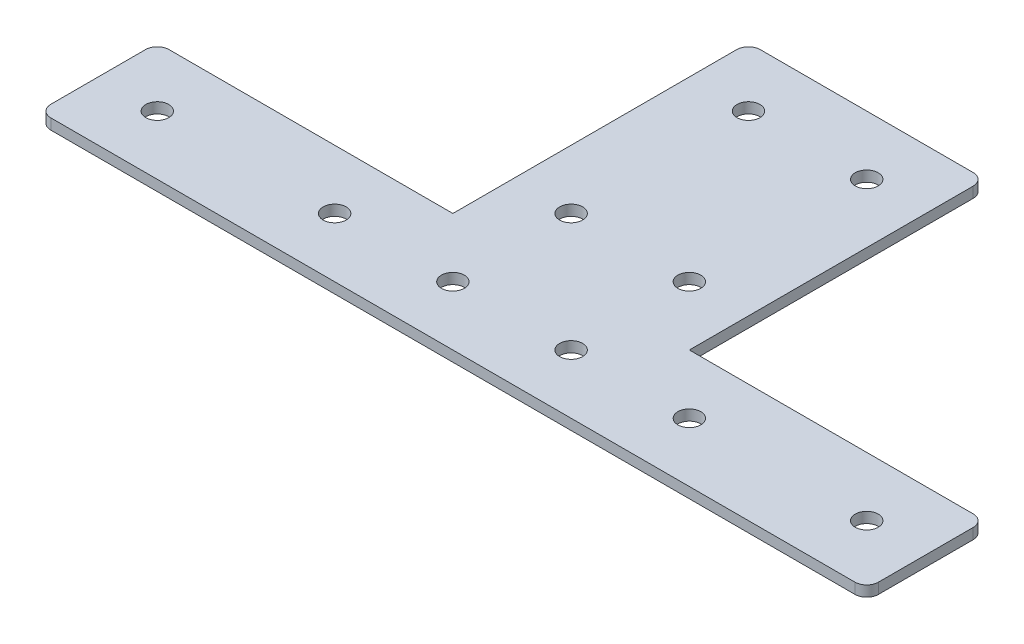
SolidWorks part; units mm, degrees
material "1060 Alloy"
ref_plane "Front Plane" through (0, 0, 0) normal (0, 0, 1) x (1, 0, 0)
ref_plane "Top Plane" through (0, 0, 0) normal (0, 1, 0) x (1, 0, 0)
ref_plane "Right Plane" through (0, 0, 0) normal (1, 0, 0) x (0, 0, -1)
sketch "Sketch1" plane through (0, 0, 0) normal (0, 1, 0) x (1, 0, 0)
  line L1 (0, 0) -> (88.9, 0)
  line L2 (0, 88.9) -> (0, 0)
  line L3 (12.7, 88.9) -> (12.7, 0) construction
  line L8 (25.4, 25.4) -> (88.9, 25.4)
  line L9 (88.9, 0) -> (88.9, 25.4)
  line L12 (0, 88.9) -> (25.4, 88.9)
  line L13 (25.4, 25.4) -> (25.4, 88.9)
  dimension "D1" = 25.4
  dimension "D2" = 88.9
extrude "Boss-Extrude1" add sketch "Sketch1" along normal blind 2.286
ref_plane "Plane1" through (12.7, 0, 0) normal (-1, 0, 0) x (0, 0, 1)
sketch "Sketch3" plane through (0, 2.286, 0) normal (0, 1, 0) x (1, 0, 0)
  line L0 (0, 12.7) -> (88.9, 12.7) construction
  line L1 (0, 88.9) -> (0, 0) construction
  line L2 (88.9, 0) -> (88.9, 25.4) construction
  line L3 (12.7, 88.9) -> (12.7, 0) construction
  line L4 (25.4, 88.9) -> (0, 88.9) construction
  line L5 (0, 0) -> (88.9, 0) construction
  circle A0 centre (76.2, 12.7) radius 2.4638
  circle A1 centre (12.7, 12.7) radius 2.4638
  circle A2 centre (12.7, 76.2) radius 2.4638
  circle A3 centre (12.7, 38.1) radius 2.4638
  circle A4 centre (38.1, 12.7) radius 2.4638
  dimension "D1" = 4.9276
  dimension "D2" = 12.7
  dimension "D3" = 12.7
  dimension "D4" = 25.4
  dimension "D5" = 25.4
extrude "Cut-Extrude2" cut sketch "Sketch3" against normal through all
mirror "Mirror1" about plane through (0, 2.286, -88.9) normal (1, 0, 0) of "Cut-Extrude2", "Boss-Extrude1"
fillet "Fillet1" radius 2.54 6 edges at (88.9, 1.143, -25.4) (88.9, 1.143, 0) (-88.9, 1.143, 0) (-88.9, 1.143, -25.4) (-25.4, 1.143, -88.9) (25.4, 1.143, -88.9)
